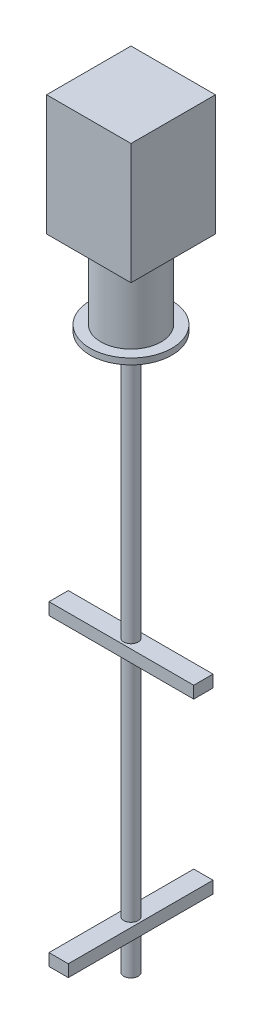
SolidWorks part; units mm, degrees
ref_plane "Front Plane" through (0, 0, 0) normal (0, 0, 1) x (1, 0, 0)
ref_plane "Top Plane" through (0, 0, 0) normal (0, 1, 0) x (1, 0, 0)
ref_plane "Right Plane" through (0, 0, 0) normal (1, 0, 0) x (0, 0, -1)
other "Configuration Table"
sketch "Sketch1" plane through (0, 0, 0) normal (0, 1, 0) x (1, 0, 0)
  circle A0 centre (0, 0) radius 170
  circle A1 centre (0, 0) radius 100
extrude "Boss-Extrude1" add sketch "Sketch1" along normal blind 25
sketch "Sketch2" plane through (0, 0, 0) normal (0, 1, 0) x (1, 0, 0)
  circle A0 centre (0, 0) radius 125
extrude "Boss-Extrude2" add sketch "Sketch2" along normal blind 325 from offset 25
sketch "Sketch3" plane through (0, 0, 0) normal (0, 1, 0) x (1, 0, 0)
  line L1 (-175, -175) -> (175, -175)
  line L2 (-175, -175) -> (-175, 175)
  line L3 (-175, 175) -> (175, 175)
  line L4 (175, -175) -> (175, 175)
extrude "Boss-Extrude3" add sketch "Sketch3" along normal blind 500 from offset 350
sketch "Sketch4" plane through (0, 0, 0) normal (0, 1, 0) x (1, 0, 0)
  circle A0 centre (0, 0) radius 30
extrude "Boss-Extrude4" add sketch "Sketch4" against normal blind 2300 flip side to cut
sketch "Sketch5" plane through (0, 0, 0) normal (0, 1, 0) x (1, 0, 0)
  line L1 (-300, -40) -> (300, -40)
  line L2 (-300, -40) -> (-300, 40)
  line L3 (-300, 40) -> (300, 40)
  line L4 (300, -40) -> (300, 40)
extrude "Boss-Extrude5" add sketch "Sketch5" against normal blind 50 from offset 1100 flip side to cut
sketch "Sketch6" plane through (0, 0, 0) normal (0, 1, 0) x (1, 0, 0)
  line L1 (-40, -300) -> (40, -300)
  line L2 (-40, -300) -> (-40, 300)
  line L3 (-40, 300) -> (40, 300)
  line L4 (40, -300) -> (40, 300)
extrude "Boss-Extrude6" add sketch "Sketch6" against normal blind 50 from offset 2100 flip side to cut
